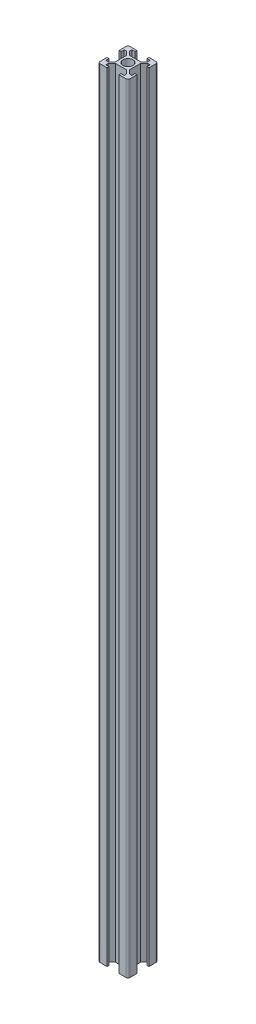
SolidWorks part; units mm, degrees
ref_plane "Front Plane" through (0, 0, 0) normal (0, 0, 1) x (1, 0, 0)
ref_plane "Top Plane" through (0, 0, 0) normal (0, 1, 0) x (1, 0, 0)
ref_plane "Right Plane" through (0, 0, 0) normal (1, 0, 0) x (0, 0, -1)
sketch "Sketch1" plane through (0, 0, 0) normal (0, 1, 0) x (1, 0, 0)
  line L0 (-7.5, -3) -> (-7.5, -6.5)
  line L5 (-6.5, -7.5) -> (-3, -7.5)
  line L6 (-7.5, -3) -> (-6.5, -3)
  line L7 (-3, -7.5) -> (-3, -6.5)
  line L8 (-6.5, -3) -> (-6.5, -4.6)
  line L9 (-3, -6.5) -> (-4.6, -6.5)
  line L10 (-6.5, -4.6) -> (-5.3071, -4.6)
  line L11 (-4.6, -6.5) -> (-4.6, -5.3071)
  line L13 (-3.5071, 0) -> (-3.5071, -2.8)
  line L14 (-3.5071, -2.8) -> (-5.3071, -4.6)
  line L16 (0, -3.5071) -> (-2.8, -3.5071)
  line L17 (-2.8, -3.5071) -> (-4.6, -5.3071)
  line L18 (-3.5071, 2.8) -> (-5.3071, 4.6)
  line L19 (-6.5, 4.6) -> (-5.3071, 4.6)
  line L20 (-6.5, 3) -> (-6.5, 4.6)
  line L21 (-7.5, 3) -> (-6.5, 3)
  line L22 (-7.5, 6.5) -> (-7.5, 3)
  line L23 (-3, 7.5) -> (-6.5, 7.5)
  line L24 (-3, 7.5) -> (-3, 6.5)
  line L25 (-3, 6.5) -> (-4.6, 6.5)
  line L26 (-4.6, 6.5) -> (-4.6, 5.3071)
  line L27 (-2.8, 3.5071) -> (-4.6, 5.3071)
  line L28 (0, 3.5071) -> (-2.8, 3.5071)
  line L31 (-3.5071, 0) -> (-3.5071, 2.8)
  line L32 (2.8, 3.5071) -> (4.6, 5.3071)
  line L33 (4.6, 6.5) -> (4.6, 5.3071)
  line L34 (3, 6.5) -> (4.6, 6.5)
  line L35 (3, 7.5) -> (3, 6.5)
  line L36 (6.5, 7.5) -> (3, 7.5)
  line L37 (7.5, 3) -> (7.5, 6.5)
  line L38 (7.5, 3) -> (6.5, 3)
  line L39 (6.5, 3) -> (6.5, 4.6)
  line L40 (6.5, 4.6) -> (5.3071, 4.6)
  line L41 (3.5071, 2.8) -> (5.3071, 4.6)
  line L42 (3.5071, 0) -> (3.5071, 2.8)
  line L45 (0, 3.5071) -> (2.8, 3.5071)
  line L46 (3.5071, -2.8) -> (5.3071, -4.6)
  line L47 (6.5, -4.6) -> (5.3071, -4.6)
  line L48 (6.5, -3) -> (6.5, -4.6)
  line L49 (7.5, -3) -> (6.5, -3)
  line L50 (7.5, -6.5) -> (7.5, -3)
  line L51 (3, -7.5) -> (6.5, -7.5)
  line L52 (3, -7.5) -> (3, -6.5)
  line L53 (3, -6.5) -> (4.6, -6.5)
  line L54 (4.6, -6.5) -> (4.6, -5.3071)
  line L55 (2.8, -3.5071) -> (4.6, -5.3071)
  line L56 (0, -3.5071) -> (2.8, -3.5071)
  line L59 (3.5071, 0) -> (3.5071, -2.8)
  arc A1 (-6.5, -7.5) -> (-7.5, -6.5) centre (-6.5, -6.5) cw
  arc A2 (-2.5, 0) -> (0, -2.5) centre (0, 0) ccw
  arc A3 (-7.5, 6.5) -> (-6.5, 7.5) centre (-6.5, 6.5) cw
  arc A4 (0, 2.5) -> (-2.5, 0) centre (0, 0) ccw
  arc A5 (6.5, 7.5) -> (7.5, 6.5) centre (6.5, 6.5) cw
  arc A6 (2.5, 0) -> (0, 2.5) centre (0, 0) ccw
  arc A7 (7.5, -6.5) -> (6.5, -7.5) centre (6.5, -6.5) cw
  arc A8 (0, -2.5) -> (2.5, 0) centre (0, 0) ccw
  point P8 (-7.5, -3)
  point P9 (-3, -7.5)
  point P75 (0, 0)
  dimension "D1" = 1
  dimension "D9" = 2.5
  dimension "D2" = 3
  dimension "D3" = 7.5
  dimension "D4" = 3
  dimension "D5" = 1
  dimension "D6" = 1
  dimension "D7" = 1.6
  dimension "D8" = 2.8
  dimension "D10" = 1
  dimension "D11" = 4
extrude "Boss-Extrude1" add sketch "Sketch1" along normal blind 390
